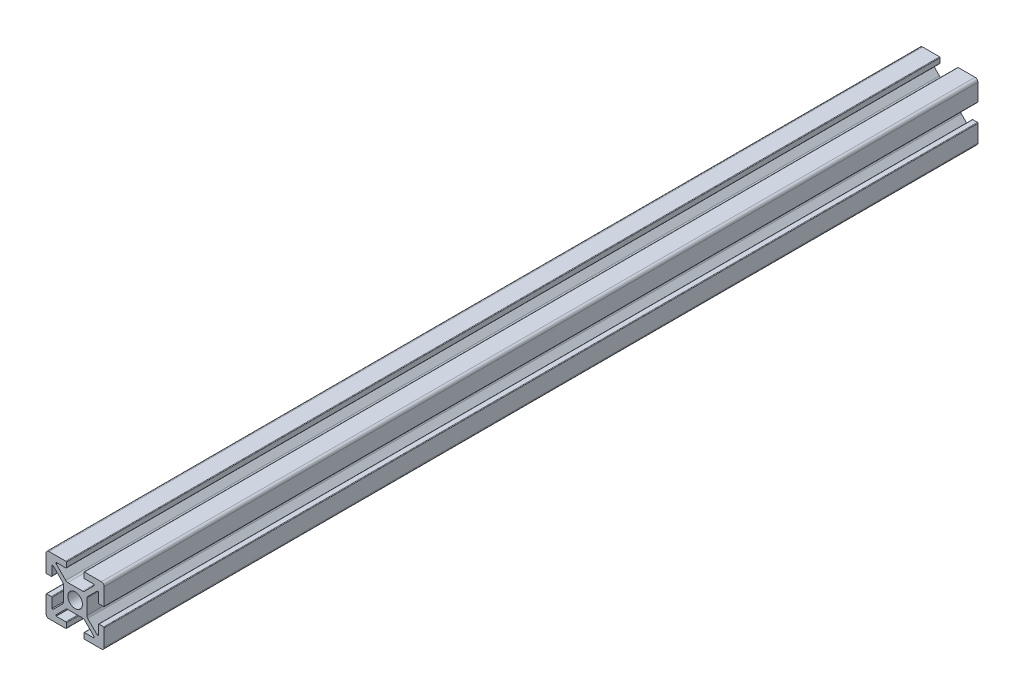
SolidWorks part; units mm, degrees
ref_plane "Front Plane" through (0, 0, 0) normal (0, 0, 1) x (1, 0, 0)
ref_plane "Top Plane" through (0, 0, 0) normal (0, 1, 0) x (1, 0, 0)
ref_plane "Right Plane" through (0, 0, 0) normal (1, 0, 0) x (0, 0, -1)
sketch "Sketch1" plane through (0, 0, 0) normal (0, 0, 1) x (1, 0, 0)
  line L0 (0.2, 13) -> (1.8, 13)
  line L1 (13.2, 0) -> (19, 0)
  line L2 (0, 13.2) -> (0, 19)
  line L3 (1, 20) -> (6.8, 20)
  line L4 (20, 1) -> (20, 6.8)
  line L5 (2, 13.2) -> (2, 16.5)
  line L6 (2, 16.5) -> (2.4393, 16.5)
  line L7 (2.4393, 16.5) -> (5.7071, 13.2322)
  line L8 (6, 12.5251) -> (6, 7.4749)
  line L11 (7.4749, 14) -> (10, 14)
  line L12 (3.5, 17.5607) -> (6.7678, 14.2929)
  line L13 (3.5, 18) -> (3.5, 17.5607)
  line L14 (6.8, 18) -> (3.5, 18)
  line L15 (6.8, 20) -> (1, 20)
  line L16 (7, 19.8) -> (7, 18.2)
  line L17 (19.8, 7) -> (18.2, 7)
  line L18 (20, 6.8) -> (20, 1)
  line L19 (18, 6.8) -> (18, 3.5)
  line L20 (18, 3.5) -> (17.5607, 3.5)
  line L21 (17.5607, 3.5) -> (14.2929, 6.7678)
  line L22 (14, 7.4749) -> (14, 12.5251)
  line L23 (12.5251, 6) -> (10, 6)
  line L24 (16.5, 2.4393) -> (13.2322, 5.7071)
  line L25 (16.5, 2) -> (16.5, 2.4393)
  line L26 (13.2, 2) -> (16.5, 2)
  line L27 (13.2, 0) -> (19, 0)
  line L28 (13, 0.2) -> (13, 1.8)
  line L30 (13, 19.8) -> (13, 18.2)
  line L31 (13.2, 20) -> (19, 20)
  line L32 (13.2, 18) -> (16.5, 18)
  line L33 (16.5, 18) -> (16.5, 17.5607)
  line L34 (16.5, 17.5607) -> (13.2322, 14.2929)
  line L35 (12.5251, 14) -> (10, 14)
  line L36 (17.5607, 16.5) -> (14.2929, 13.2322)
  line L37 (18, 16.5) -> (17.5607, 16.5)
  line L38 (18, 13.2) -> (18, 16.5)
  line L39 (20, 13.2) -> (20, 19)
  line L40 (19.8, 13) -> (18.2, 13)
  line L41 (7, 0.2) -> (7, 1.8)
  line L42 (6.8, 0) -> (1, 0)
  line L43 (6.8, 2) -> (3.5, 2)
  line L44 (3.5, 2) -> (3.5, 2.4393)
  line L45 (3.5, 2.4393) -> (6.7678, 5.7071)
  line L46 (7.4749, 6) -> (10, 6)
  line L47 (2.4393, 3.5) -> (5.7071, 6.7678)
  line L48 (2, 3.5) -> (2.4393, 3.5)
  line L49 (2, 6.8) -> (2, 3.5)
  line L50 (20, 19) -> (20, 13.2)
  line L51 (1, 0) -> (6.8, 0)
  line L52 (0, 6.8) -> (0, 1)
  line L53 (13.2, 20) -> (19, 20)
  line L54 (0.2, 7) -> (1.8, 7)
  arc A0 (20, 1) -> (19, 0) centre (19, 1) cw
  arc A1 (1, 0) -> (0, 1) centre (1, 1) cw
  arc A2 (0, 19) -> (1, 20) centre (1, 19) cw
  arc A3 (20, 19) -> (19, 20) centre (19, 19) ccw
  arc A4 (14.2929, 6.7678) -> (14, 7.4749) centre (15, 7.4749) cw
  arc A5 (12.5251, 6) -> (13.2322, 5.7071) centre (12.5251, 5) cw
  arc A6 (6.7678, 5.7071) -> (7.4749, 6) centre (7.4749, 5) cw
  arc A7 (5.7071, 6.7678) -> (6, 7.4749) centre (5, 7.4749) ccw
  arc A8 (14.2929, 13.2322) -> (14, 12.5251) centre (15, 12.5251) ccw
  arc A9 (13.2322, 14.2929) -> (12.5251, 14) centre (12.5251, 15) cw
  arc A10 (6, 12.5251) -> (5.7071, 13.2322) centre (5, 12.5251) ccw
  arc A11 (7.4749, 14) -> (6.7678, 14.2929) centre (7.4749, 15) cw
  arc A12 (0, 6.8) -> (0.2, 7) centre (0.2, 6.8) cw
  arc A13 (2, 6.8) -> (1.8, 7) centre (1.8, 6.8) ccw
  arc A14 (7, 1.8) -> (6.8, 2) centre (6.8, 1.8) ccw
  arc A15 (7, 0.2) -> (6.8, 0) centre (6.8, 0.2) cw
  arc A16 (13.2, 0) -> (13, 0.2) centre (13.2, 0.2) cw
  arc A17 (13.2, 2) -> (13, 1.8) centre (13.2, 1.8) ccw
  arc A18 (18.2, 7) -> (18, 6.8) centre (18.2, 6.8) ccw
  arc A19 (19.8, 7) -> (20, 6.8) centre (19.8, 6.8) cw
  arc A20 (20, 13.2) -> (19.8, 13) centre (19.8, 13.2) cw
  arc A21 (18, 13.2) -> (18.2, 13) centre (18.2, 13.2) ccw
  arc A22 (13, 19.8) -> (13.2, 20) centre (13.2, 19.8) cw
  arc A23 (13, 18.2) -> (13.2, 18) centre (13.2, 18.2) ccw
  arc A24 (6.8, 18) -> (7, 18.2) centre (6.8, 18.2) ccw
  arc A25 (7, 19.8) -> (6.8, 20) centre (6.8, 19.8) ccw
  arc A26 (1.8, 13) -> (2, 13.2) centre (1.8, 13.2) ccw
  arc A27 (0.2, 13) -> (0, 13.2) centre (0.2, 13.2) cw
  circle A28 centre (10, 10) radius 2.5
  point P19 (2, 13)
  dimension "D1" = 1
  dimension "D4" = 1
  dimension "D5" = 0.2
  dimension "D6" = 0.2
  dimension "D7" = 5
  dimension "D2" = 7
  dimension "D3" = 2
  dimension "D9" = 3.5
extrude "Boss-Extrude1" add sketch "Sketch1" along normal blind 300 contours A27 L0 A26 L5 L6 L7 A10 L8 A7 L47 L48 L49 A13 L54 A12 L52 A1 L42 A15 L41 A14 L43 L44 L45 A6 L46 L23 A5 L24 L25 L26 A17 L28 A16 L1 A0 L4 A19 L17 A18 L19 L20 L21 A4 L22 A8 L36 L37 L38 A21 L40
